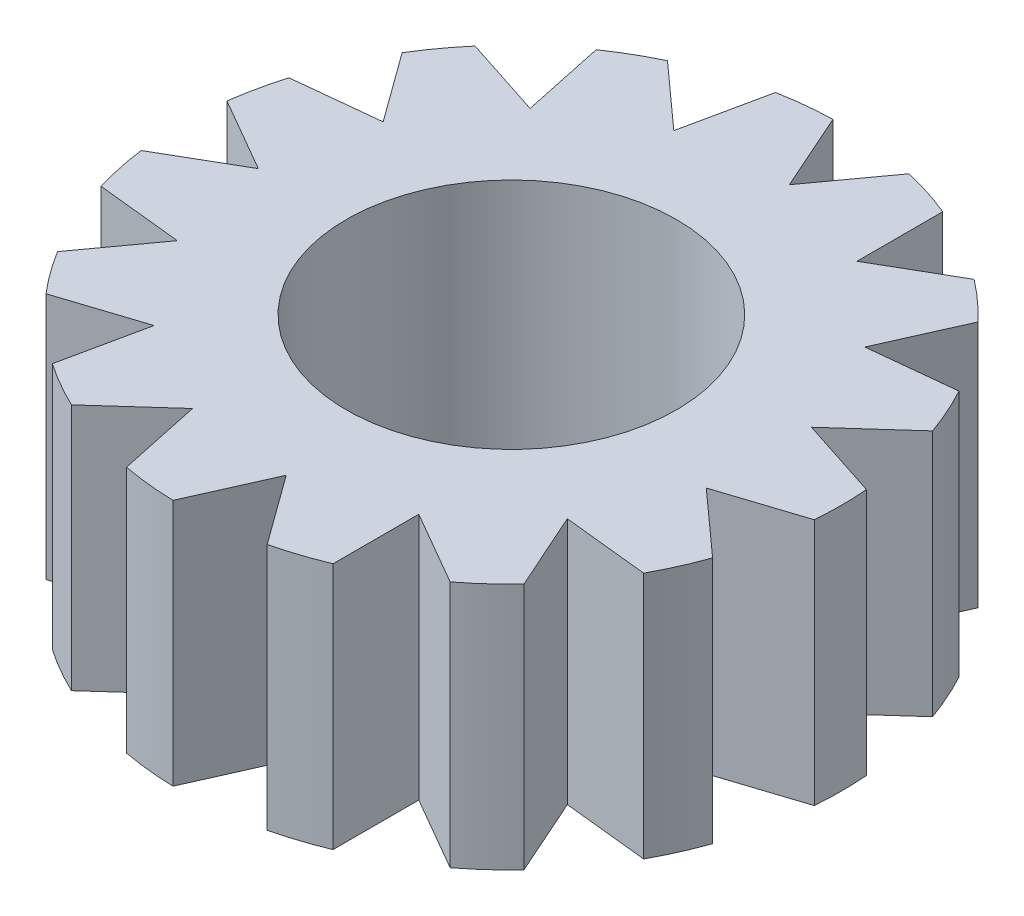
SolidWorks part; units mm, degrees
ref_plane "前视基准面" through (0, 0, 0) normal (0, 0, 1) x (1, 0, 0)
ref_plane "上视基准面" through (0, 0, 0) normal (0, 1, 0) x (1, 0, 0)
ref_plane "右视基准面" through (0, 0, 0) normal (1, 0, 0) x (0, 0, -1)
sketch "草图2" plane through (0, 0, 0) normal (0, 0, 1) x (1, 0, 0)
  line L0 (0, 0) -> (0, 32.2759) construction
  line L1 (0, 0) -> (32.2759, 0) construction
  line L3 (-40, 30) -> (-20, 30)
  line L4 (-40, 30) -> (-40, 0)
  line L5 (-40, 0) -> (-20, 0)
  line L6 (-20, 30) -> (-20, 0)
  line L7 (-40, 30) -> (-20, 0) construction
  line L8 (-40, 0) -> (-20, 30) construction
  point P3 (-30, 15)
  dimension "D1" = 30
  dimension "D2" = 20
  dimension "D3" = 30
revolve "旋转1" add sketch "草图2" angle 360 about L0
sketch "草图3" plane through (0, 30, 0) normal (0, 1, 0) x (1, 0, 0)
  line L0 (0, 0) -> (30, 0) construction
  line L1 (-30.6611, 0) -> (-39.6611, 5.1962)
  line L3 (-39.6611, -5.1962) -> (-30.6611, 0)
  line L4 (-55, 0) -> (55, 0) construction
  line L5 (0, 0) -> (0, 30) construction
  line L6 (-39.6611, -5.1962) -> (-48.6611, 0)
  line L7 (-48.6611, 0) -> (-39.6611, 5.1962)
  line L8 (-39.6611, -1.7852) -> (-39.6611, -5.1962) [skipped]
  circle A1 centre (0, 0) radius 40 construction
  point P10 (0, 0)
  point P12 (0, 0)
  point P13 (0, 0)
extrude "切除-拉伸1" cut sketch "草图3" against normal through all contours L3 L1 L7 L6
pattern_circular "阵列(圆周)2" count 15 over 360 about axis through (0, 0, 0) along (0, 1, 0) of "切除-拉伸1"
